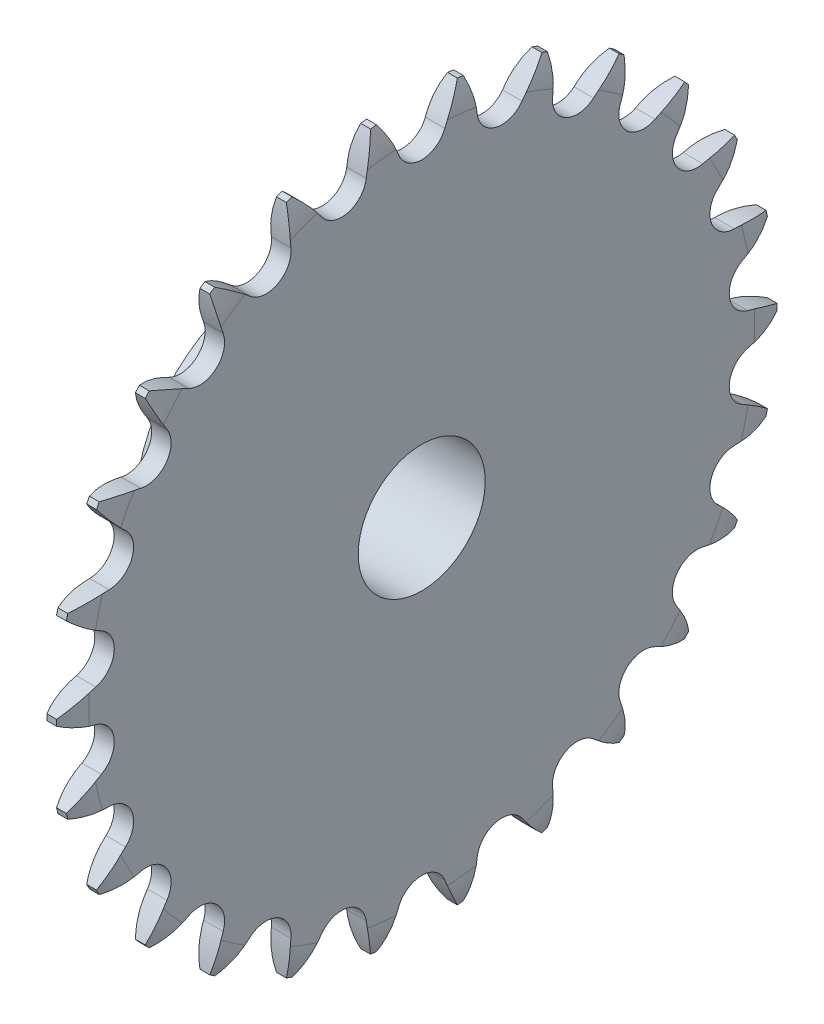
SolidWorks part; units mm, degrees
ref_plane "Plane1" through (0, 0, 0) normal (0, 0, 1) x (1, 0, 0)
ref_plane "Plane2" through (0, 0, 0) normal (0, 1, 0) x (1, 0, 0)
ref_plane "Plane3" through (0, 0, 0) normal (1, 0, 0) x (0, 0, -1)
sketch "Clipboard" plane through (0, 0, 0) normal (0, 1, 0) x (1, 0, 0)
  line L0 (0, 0) -> (11.4147, -5.5673)
  line L1 (-15, 0) -> (100, 0) construction
  line L2 (0, 0) -> (-0.5049, 0.5707)
  line L3 (0, 0) -> (-11.863, 4.5341)
  line L4 (0, 0) -> (2.7863, 1.359)
  line L5 (0, 0) -> (-23.4238, -8.7364)
  line L6 (0, 0) -> (-2.5441, -1.7165)
  line L7 (-0.5049, 0.5707) -> (21.7707, 11.9207)
  line L8 (-76.2, 38.1) -> (-73.4, 38.1)
  line L9 (-73.2427, 39.6204) -> (-72.6435, 39.6525)
  line L10 (-73.1375, 10.4807) -> (-66.1375, 10.4807)
  circle A0 centre (0, 0) radius 3.875
  circle A1 centre (0, 0) radius 21
  circle A2 centre (0, 0) radius 21
  dimension "Dr" = 7.75
  dimension "MHD" = 42
  dimension "Hub_dia" = 42
  dimension "Num_teeth" = 26
  dimension "Pitch" = 12.7
  dimension "Width" = 3.1
  dimension "Side_relief" = 0.762
  dimension "Side_radius" = 12.7
  dimension "Overall_len" = 25
  dimension "Show_teeth" = 26
  dimension "Thickness" = 3.069
  dimension "OAL" = 25.0005
  dimension "T_dim" = 2.8
  dimension "Fillet_rad" = 0.6
  dimension "Face_width" = 3.069
  dimension "Num_strands" = 1
  dimension "Transv_pitch" = 7
  dimension "Plate_wid" = 9.91
sketch "BasProSke" plane through (0, 0, 0) normal (0, 1, 0) x (1, 0, 0)
  line L0 (-10, 0) -> (60, 0) construction
  line L1 (0, 0) -> (0, 52.4106)
  line L2 (0, 0) -> (3.069, 0)
  line L3 (3.069, 0) -> (3.069, 52.4106)
  line L4 (2.307, 56.7436) -> (0.762, 56.7436)
  arc A0 (0, 52.4106) -> (0.762, 56.7436) centre (12.7, 52.4106) cw
  arc A1 (3.069, 52.4106) -> (2.307, 56.7436) centre (-9.631, 52.4106) ccw
  dimension "Thickness" = 3.069
  dimension "D1" = 12.7
  dimension "G1" = 0.762
  dimension "G2" = 0.762
  dimension "Diameter" = 113.4871
revolve "Base-Revolve" add sketch "BasProSke" angle 360 about L0
sketch "TooCutSke" plane through (0, 0, 0) normal (1, 0, 0) x (0, 0, -1)
  line L0 (0, 52.7198) -> (3.6356, 51.2708) construction
  line L1 (0, 0) -> (0, 107) construction
  line L2 (0, 52.7198) -> (-10, 52.7198) construction
  line L3 (0, 52.7198) -> (-3.6356, 51.2708) construction
  arc A0 (3.6356, 51.2708) -> (6.6968, 56.8505) centre (27.8251, 41.6296) cw
  arc A1 (3.6356, 51.2708) -> (-3.6356, 51.2708) centre (0, 52.7198) cw
  arc A2 (-3.6356, 51.2708) -> (-6.6968, 56.8505) centre (-27.8251, 41.6296) ccw
  arc A3 (6.6968, 56.8505) -> (-6.6968, 56.8505) centre (0, 0) ccw
  dimension "R1" = 3.9137
  dimension "R2" = 26.04
  dimension "Overcut" = 57.2436
  dimension "Seat_radius" = 52.7198
  dimension "X" = 136.538
extrude "ToothCut" cut sketch "TooCutSke" along normal through all
pattern_circular "TeethCuts" count 26 every 13.846 about axis through (-10, 0, 0) along (1, 0, 0) of "ToothCut"
sketch "HubNeaOneSke" plane through (0, 0, 0) normal (-1, 0, 0) x (0, 0, 1)
  circle A0 centre (0, 0) radius 21
  dimension "Diameter" = 42
extrude "HubNearOne" add sketch "HubNeaOneSke" along normal blind 24
fillet "HubNearOneFillet" radius 0.6 1 edges at (0, 0, -21)
sketch "HubNeaBotSke" plane through (0, 0, 0) normal (-1, 0, 0) x (0, 0, 1)
  circle A0 centre (0, 0) radius 21
  dimension "Diameter" = 42
extrude "HubNearBoth" [suppressed] add sketch "HubNeaBotSke" along normal blind 10.9657
fillet "HubNearBothFillet" [suppressed] radius 0.6
ref_plane "FarPln" through (3.069, 0, 0) normal (1, 0, 0) x (0, 0, -1)
sketch "HubFarSke" plane through (3.069, 0, 0) normal (1, 0, 0) x (0, 0, -1)
  circle A0 centre (0, 0) radius 21
  dimension "Diameter" = 42
extrude "HubFar" [suppressed] add sketch "HubFarSke" along normal blind 10.9657
fillet "HubFarFillet" [suppressed] radius 0.6
sketch "BorSke" plane through (0, 0, 0) normal (1, 0, 0) x (0, 0, -1)
  circle A0 centre (0, 0) radius 10
  dimension "Diameter" = 20
extrude "Bore" cut sketch "BorSke" along normal mid plane 50.001
sketch "KeySke" plane through (0, 0, 0) normal (1, 0, 0) x (0, 0, -1)
  line L0 (-3, 0) -> (-3, 12.8)
  line L1 (-3, 12.8) -> (3, 12.8)
  line L2 (3, 12.8) -> (3, 0)
  line L3 (0, 0) -> (0, 34) construction
  line L4 (-3, 0) -> (3, 0)
  dimension "Offset" = 12.8
  dimension "Width" = 6
extrude "Keyway" [suppressed] cut sketch "KeySke" along normal mid plane 50.001
pattern_circular "Keyway2" [suppressed] count 2 every 90 about axis through (-10, 0, 0) along (1, 0, 0)
sketch "Эскиз1" plane through (0, 0, 0) normal (0, 0, 1) x (1, 0, 0)
  line L0 (-0.6, 21) -> (-24, 21) construction
  line L1 (-15, 21) -> (-7, 21)
  line L2 (-15, 21) -> (-15, 13)
  line L3 (-15, 13) -> (-7, 13)
  line L4 (-7, 21) -> (-7, 13)
  line L5 (-15, 21) -> (-7, 13) construction
  line L6 (-15, 13) -> (-7, 21) construction
  point P0 (-11, 17)
  point P8 (-11, 21)
  dimension "D1" = 9
  dimension "D2" = 8
  dimension "D3" = 8
sweep "Вырез-По траектории1" cut profiles "Эскиз1" path edge at (-24, 0, 21)
chamfer "Фаска1" distance 3 angle 74 1 edges at (-24, 0, 21)
sketch "Эскиз2" plane through (0, 0, 0) normal (0, 1, 0) x (1, 0, 0)
  line L1 (-24, 10.5378) -> (-24, -10.5378) construction
  line L2 (-21.9, -4.1) -> (-36.7968, -4.1)
  line L3 (-36.7968, -4.1) -> (-36.7968, 3.9208)
  line L4 (-36.7968, 3.9208) -> (-21.9, 4.1)
  arc A0 (-21.9, -4.1) -> (-21.9, 4.1) centre (-21.9, 0) ccw
  dimension "D1" = 4.1
  dimension "D2" = 2
extrude "Вырез-Вытянуть2" cut sketch "Эскиз2" against normal through all both and the other way through all contours L2 L3 L4 A0
equation "' \"Pitch@Clipboard\" = 12.7"
equation "' \"Num_strands@Clipboard\" = 1"
equation "' \"Num_teeth@Clipboard\" = 9"
equation "' \"Hub_dia@Clipboard\" = 50"
equation "' \"Overall_len@Clipboard\" = 3"
equation "' \"Diameter@BorSke\" = 12"
equation "' \"T_dim@Clipboard\" = 1"
equation "' \"Width@KeySke\" = 2"
equation "' \"Dr@Clipboard\" = 8.51"
equation "' \"Face_width@Clipboard\" = 7.2"
equation "' \"Side_radius@Clipboard\" = 12.7"
equation "' \"Side_relief@Clipboard\" = 1.27"
equation "' \"Transv_pitch@Clipboard\" = 13.92"
equation "' \"Show_teeth@Clipboard\" = 9"
equation "' \"Fillet_rad@Clipboard\" = 0.6"
equation "' \"Plate_wid@Clipboard\" = 11.8"
equation "\"Num_teeth@Clipboard\" = int( \"Num_teeth@Clipboard\" )"
equation "\"Num_teeth@Clipboard\" = ((sgn( \"Num_teeth@Clipboard\" - 5.0)+1)*( \"Num_teeth@Clipboard\" - 5.0))/2 +5.0"
equation "\"Num_teeth@Clipboard\" = ((sgn( \"Num_teeth@Clipboard\" - 200.0)-1)*( \"Num_teeth@Clipboard\" - 200.0))/-2 +200.0"
equation "\"MHD@Clipboard\" = \"Pitch@Clipboard\" * (1.0 / tan(3.14159265 / \"Num_teeth@Clipboard\" )) - 1.04 * \"Plate_wid@Clipboard\" - 0.76"
equation "\"Thickness@Clipboard\"  = \"Face_width@Clipboard\" + (\"Num_strands@Clipboard\" - 1) * \"Transv_pitch@Clipboard\""
equation "\"OAL@Clipboard\" = \"Thickness@Clipboard\" + 2 * \"Fillet_rad@Clipboard\" + 1"
equation "\"MHD@Clipboard\" = ((sgn( \"MHD@Clipboard\" - \"Hub_dia@Clipboard\" )-1)*( \"MHD@Clipboard\" - \"Hub_dia@Clipboard\" ))/-2+ \"Hub_dia@Clipboard\""
equation "\"OAL@Clipboard\" = ((sgn( \"OAL@Clipboard\" - \"Overall_len@Clipboard\" )+1)*( \"OAL@Clipboard\" - \"Overall_len@Clipboard\" ))/2 + \"Overall_len@Clipboard\" + 0.0005"
equation "\"Num_teeth@TeethCuts\" = int( \"Show_teeth@Clipboard\" ) + 1"
equation "\"Num_teeth@TeethCuts\" = ((sgn( \"Num_teeth@TeethCuts\" - \"Num_teeth@Clipboard\" )-1)*( \"Num_teeth@TeethCuts\" - \"Num_teeth@Clipboard\" ))/-2+ \"Num_teeth@Clipboard\""
equation "\"Num_teeth@TeethCuts\" = ((sgn( \"Num_teeth@TeethCuts\" - 2.0)+1)*( \"Num_teeth@TeethCuts\" - 2.0))/2 +2.0"
equation "\"Angle@TeethCuts\" = 360.0 / \"Num_teeth@Clipboard\""
equation "\"Seat_radius@TooCutSke\" = ( \"Pitch@Clipboard\" / 2.0) / sin(3.14159265 / \"Num_teeth@Clipboard\" ) - \"Dr@Clipboard\" / 2.0 + \"Dr@Clipboard\" * 0.505"
equation "\"R1@TooCutSke\"  = \"Dr@Clipboard\" * 0.505"
equation "\"X@TooCutSke\" = 140.0 - (90.0 / \"Num_teeth@Clipboard\")"
equation "\"R2@TooCutSke\" = 0.12 * \"Dr@Clipboard\" * ( \"Num_teeth@Clipboard\" + 2.0)"
equation "\"Overcut@TooCutSke\" = 0.5 + 0.625 * \"Pitch@Clipboard\" - 0.5 * \"Dr@Clipboard\"  +  \"Pitch@Clipboard\" / 2.0 / sin(3.14159265 / \"Num_teeth@Clipboard\" )"
equation "\"Diameter@BasProSke\" = 2.0 * ( 0.625 * \"Pitch@Clipboard\" - 0.5 * \"Dr@Clipboard\"  +  \"Pitch@Clipboard\" / 2.0 / sin(3.14159265 / \"Num_teeth@Clipboard\" ))"
equation "\"Thickness@BasProSke\"  = \"Thickness@Clipboard\""
equation "\"G1@BasProSke\" =  \"Side_relief@Clipboard\""
equation "\"G2@BasProSke\" =  \"Side_relief@Clipboard\""
equation "\"D1@BasProSke\" =  \"Side_radius@Clipboard\""
equation "\"Diameter@HubNeaOneSke\" = \"MHD@Clipboard\""
equation "\"Diameter@HubNeaBotSke\" = \"MHD@Clipboard\""
equation "\"Length@HubNearBoth\" = ( \"OAL@Clipboard\" - \"Thickness@BasProSke\" ) / 2.0"
equation "\"D1@HubNearOneFillet\" = \"Fillet_rad@Clipboard\""
equation "\"D1@HubNearBothFillet\" = \"Fillet_rad@Clipboard\""
equation "\"Thickness@FarPln\" = \"Thickness@BasProSke\""
equation "\"Diameter@HubFarSke\" = \"MHD@Clipboard\""
equation "\"Length@HubFar\" = ( \"OAL@Clipboard\" - \"Thickness@BasProSke\" ) / 2.0"
equation "\"D1@HubFarFillet\" = \"Fillet_rad@Clipboard\""
equation "\"D1@Bore\" = \"OAL@Clipboard\" * 2.0"
equation "\"D1@Keyway\" = \"OAL@Clipboard\" * 2.0"
equation "\"Offset@KeySke\" = \"T_dim@Clipboard\" + \"Diameter@BorSke\" / 2.0"
